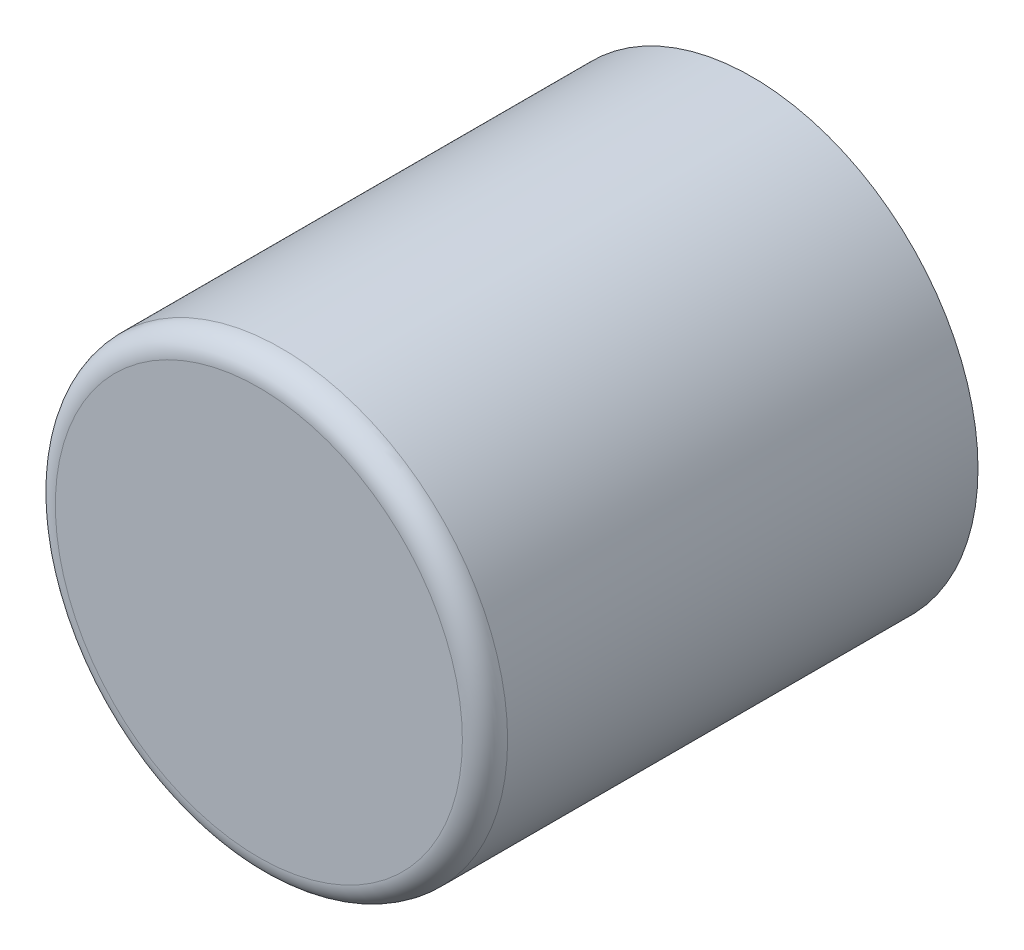
SolidWorks part; units mm, degrees
ref_plane "Front Plane" through (0, 0, 0) normal (0, 0, 1) x (1, 0, 0)
ref_plane "Top Plane" through (0, 0, 0) normal (0, 1, 0) x (1, 0, 0)
ref_plane "Right Plane" through (0, 0, 0) normal (1, 0, 0) x (0, 0, -1)
sketch "Sketch2" plane through (0, 0, 0) normal (0, 0, 1) x (1, 0, 0)
  circle A0 centre (0, 0) radius 100
  circle A1 centre (0, 0) radius 90
  dimension "D1" = 200
extrude "Boss-Extrude1" add sketch "Sketch2" against normal blind 68 and the other way blind 150 contours A0
sketch "Sketch6" plane through (0, 0, -68) normal (0, 0, -1) x (-1, 0, 0)
  circle A0 centre (0, 0) radius 90
extrude "Cut-Extrude1" cut sketch "Sketch6" against normal blind 200 and the other way blind 20 contours A0
fillet "Fillet1" radius 10 1 edges at (100, 0, 150)
